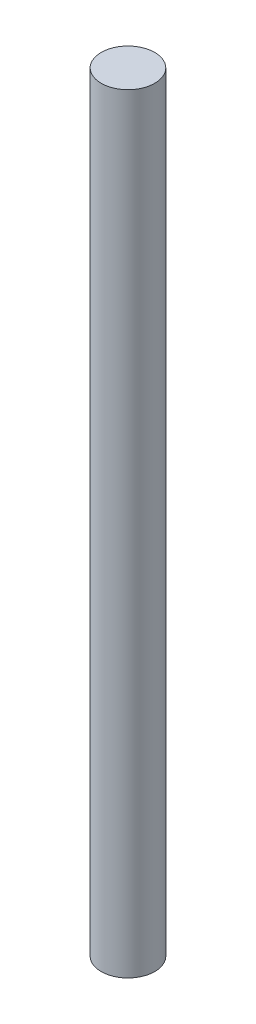
SolidWorks part; units mm, degrees
ref_plane "Alzado" through (0, 0, 0) normal (0, 0, 1) x (1, 0, 0)
ref_plane "Planta" through (0, 0, 0) normal (0, 1, 0) x (1, 0, 0)
ref_plane "Vista lateral" through (0, 0, 0) normal (1, 0, 0) x (0, 0, -1)
sketch "Croquis1" plane through (0, 0, 0) normal (0, 1, 0) x (1, 0, 0)
  circle A0 centre (0, 0) radius 4
  dimension "D1" = 8
extrude "Saliente-Extruir1" add sketch "Croquis1" along normal blind 115
